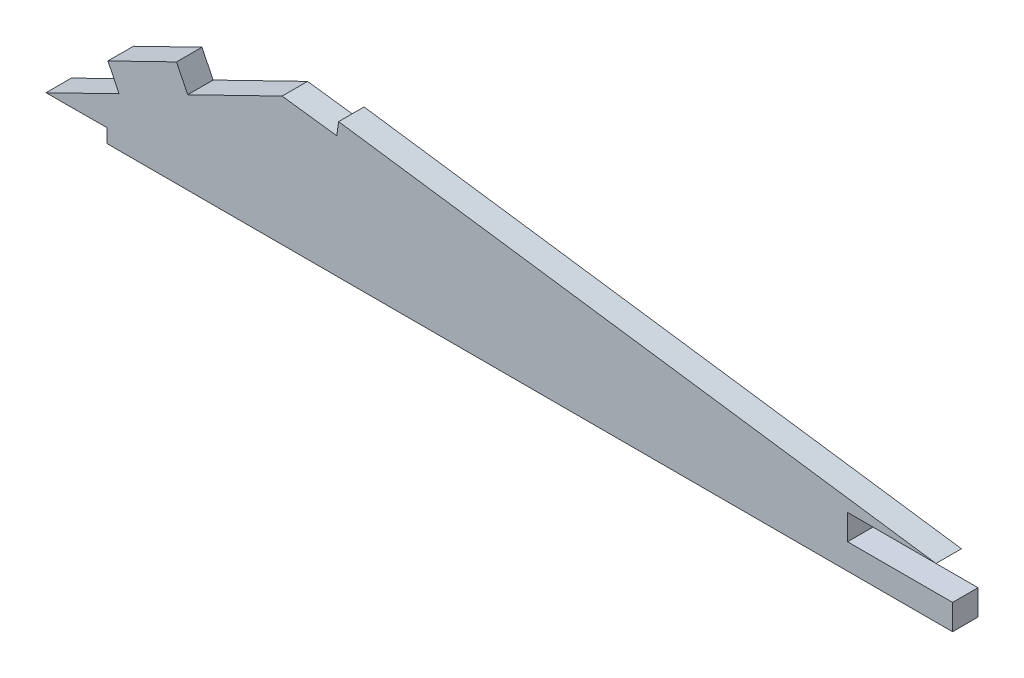
SolidWorks part; units mm, degrees
ref_plane "前视基准面" through (0, 0, 0) normal (0, 0, 1) x (1, 0, 0)
ref_plane "上视基准面" through (0, 0, 0) normal (0, 1, 0) x (1, 0, 0)
ref_plane "右视基准面" through (0, 0, 0) normal (1, 0, 0) x (0, 0, -1)
sketch "Model" plane through (0, 0, 0) normal (0, 0, 1) x (1, 0, 0)
  line L0 (7.756, 7.194) -> (6.8792, 8.9916)
  line L1 (6.8792, 8.9916) -> (12.272, 11.6218)
  line L2 (12.272, 11.6218) -> (13.1488, 9.8242)
  line L3 (7.756, 7.194) -> (2.011, 4.392)
  line L4 (13.1488, 9.8242) -> (20.5726, 13.4451)
  line L5 (6.7967, 3.3274) -> (73.2781, 3.3274)
  line L6 (6.7967, 3.3274) -> (6.7925, 4.4105)
  line L7 (6.7925, 4.4105) -> (2.011, 4.392)
  line L8 (65.0219, 5.3274) -> (73.2781, 5.3274)
  line L9 (65.0219, 7.3274) -> (71.9763, 7.3274)
  line L10 (65.0219, 5.3274) -> (65.0219, 7.3274)
  line L11 (73.2781, 3.3274) -> (73.2781, 5.3274)
  line L12 (25.0151, 13.9273) -> (71.9763, 7.3274)
  line L13 (20.5726, 13.4451) -> (24.8669, 12.8896)
  line L14 (24.8669, 12.8896) -> (25.0151, 13.9273)
extrude "凸台-拉伸1" add sketch "Model" along normal blind 2
